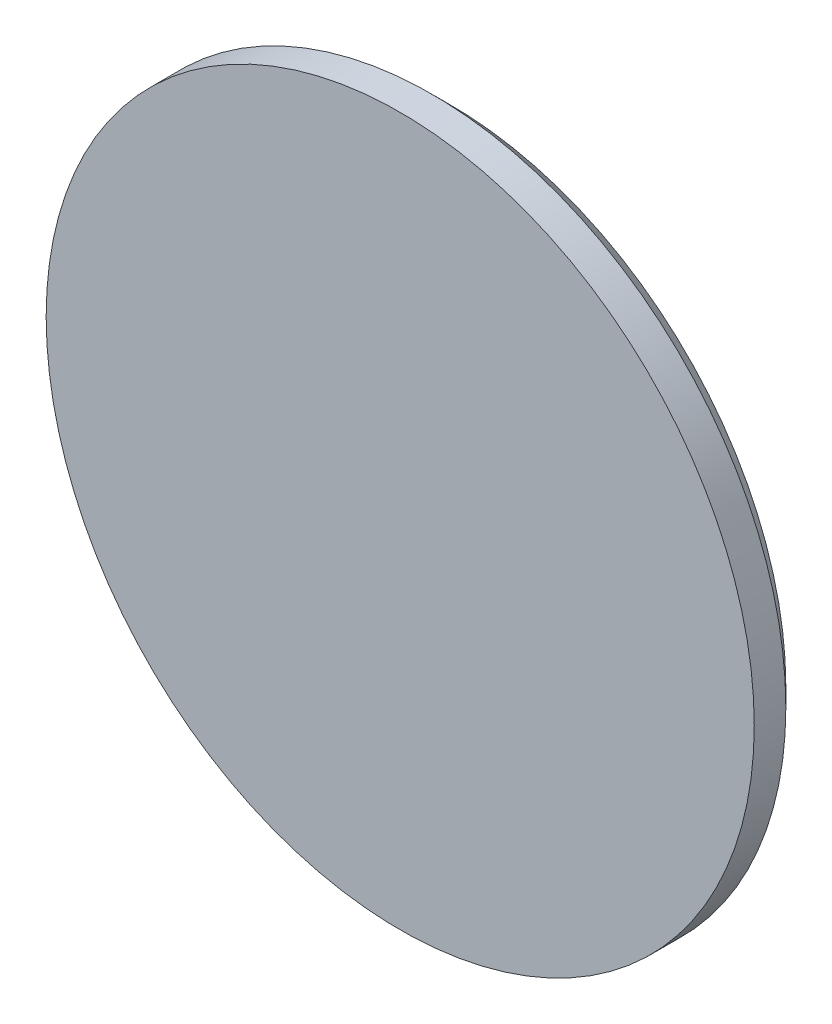
SolidWorks part; units mm, degrees
material "Plywood"
ref_plane "Front Plane" through (0, 0, 0) normal (0, 0, 1) x (1, 0, 0)
ref_plane "Top Plane" through (0, 0, 0) normal (0, 1, 0) x (1, 0, 0)
ref_plane "Right Plane" through (0, 0, 0) normal (1, 0, 0) x (0, 0, -1)
sketch "Sketch1" plane through (0, 0, 0) normal (0, 0, 1) x (1, 0, 0)
  circle A0 centre (-33.2032, 22.4395) radius 25
extrude "Boss-Extrude1" add sketch "Sketch1" along normal blind 3.5 contours A0
chamfer "Chamfer1" distance 1.27 angle 45 1 edges at (-8.2032, 22.4395, 0)
